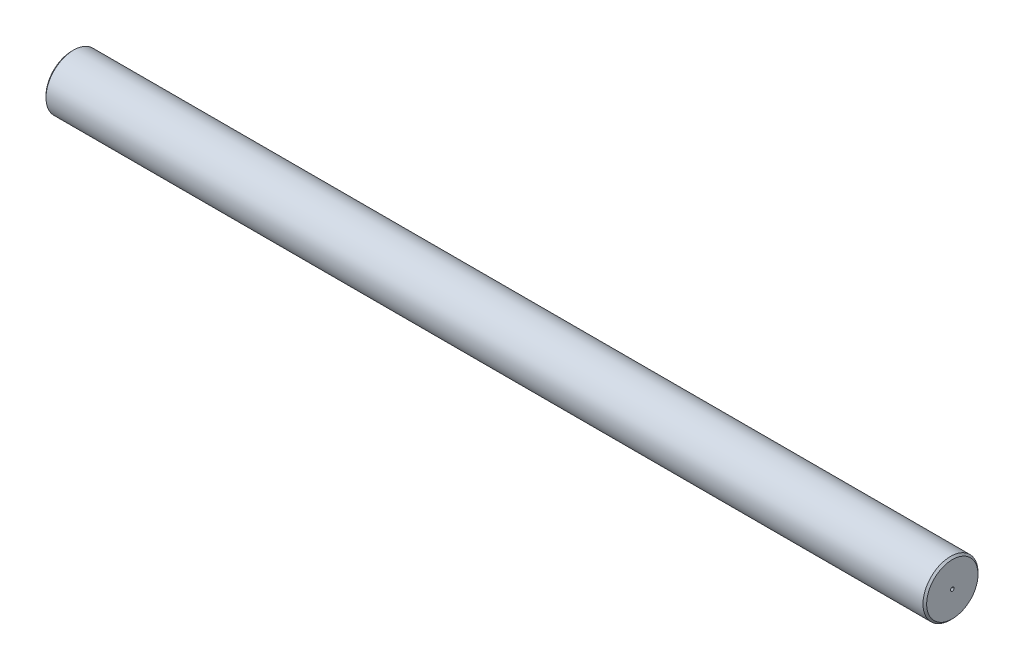
SolidWorks part; units mm, degrees
ref_plane "Front Plane" through (0, 0, 0) normal (0, 0, 1) x (1, 0, 0)
ref_plane "Top Plane" through (0, 0, 0) normal (0, 1, 0) x (1, 0, 0)
ref_plane "Right Plane" through (0, 0, 0) normal (1, 0, 0) x (0, 0, -1)
sketch "Sketch1" plane through (0, 0, 0) normal (0, 0, 1) x (1, 0, 0)
  line L0 (0, 0) -> (240, 0) construction
  line L2 (0, 7.5) -> (240, 7.5)
  line L3 (0, 7.5) -> (0, 0)
  line L4 (0, 0) -> (240, 0)
  line L5 (240, 7.5) -> (240, 0)
  dimension "L" = 240
  dimension "D_s" = 15
revolve "Revolve1" add sketch "Sketch1" angle 360 about L0
sketch "Sketch2" plane through (0, 0, 0) normal (0, 0, 1) x (1, 0, 0)
  line L0 (0, 0) -> (240, 0) construction
  line L1 (240, -7.5) -> (240, 7.5) construction
  line L2 (0, 0.5) -> (0, 0)
  line L3 (0, 0) -> (0.5, 0)
  line L4 (0, 0.5) -> (0.5, 0)
  line L5 (239.5, 0) -> (240, 0.5)
  line L6 (239.5, 0) -> (240, 0)
  line L7 (240, 0.5) -> (240, 0)
  line L8 (0, 7.5) -> (0, -7.5) construction
  dimension "D1" = 1
  dimension "D2" = 0.5
revolve "Cut-Revolve1" cut sketch "Sketch2" angle 360 about L0
chamfer "Chamfer1" distance 0.5 angle 45 2 edges at (240, -7.5, 0) (0, -7.5, 0)
